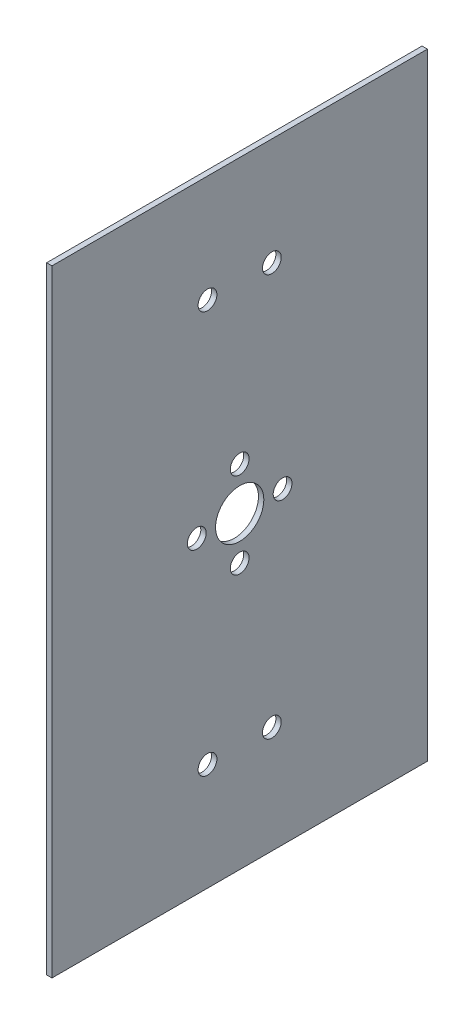
SolidWorks part; units mm, degrees
ref_plane "Front Plane" through (0, 0, 0) normal (0, 0, 1) x (1, 0, 0)
ref_plane "Top Plane" through (0, 0, 0) normal (0, 1, 0) x (1, 0, 0)
ref_plane "Right Plane" through (0, 0, 0) normal (1, 0, 0) x (0, 0, -1)
sketch "Sketch1" plane through (0, 0, 0) normal (1, 0, 0) x (0, 0, -1)
  line L0 (-35, 0) -> (35, 0) construction
  line L1 (-35, 57.5) -> (35, 57.5)
  line L2 (-35, 57.5) -> (-35, -57.5)
  line L3 (-35, -57.5) -> (35, -57.5)
  line L4 (35, 57.5) -> (35, -57.5)
  line L5 (-35, 57.5) -> (35, -57.5) construction
  line L6 (-35, -57.5) -> (35, 57.5) construction
  line L7 (0, 22.9273) -> (0, -23.2201) construction
  line L8 (-35, 37.5) -> (35, 37.5) construction
  line L9 (0, 57.5) -> (0, -57.5) construction
  circle A0 centre (0, 0) radius 4.5
  circle A1 centre (0, 8) radius 1.75
  circle A2 centre (8, 0) radius 1.75
  circle A3 centre (0, -8) radius 1.75
  circle A4 centre (-8, 0) radius 1.75
  circle A5 centre (-6, 37.5) radius 1.75
  circle A6 centre (6, 37.5) radius 1.75
  circle A7 centre (6, -37.5) radius 1.75
  circle A8 centre (-6, -37.5) radius 1.75
  point P0 (0, 0)
  point P23 (0, 0)
  dimension "D2" = 9
  dimension "D3" = 3.5
  dimension "D7" = 3.5
  dimension "D4" = 8
  dimension "D5" = 70
  dimension "D6" = 115
  dimension "D8" = 20
  dimension "D9" = 12
  dimension "D1" = 4
extrude "Boss-Extrude1" add sketch "Sketch1" along normal blind 1
